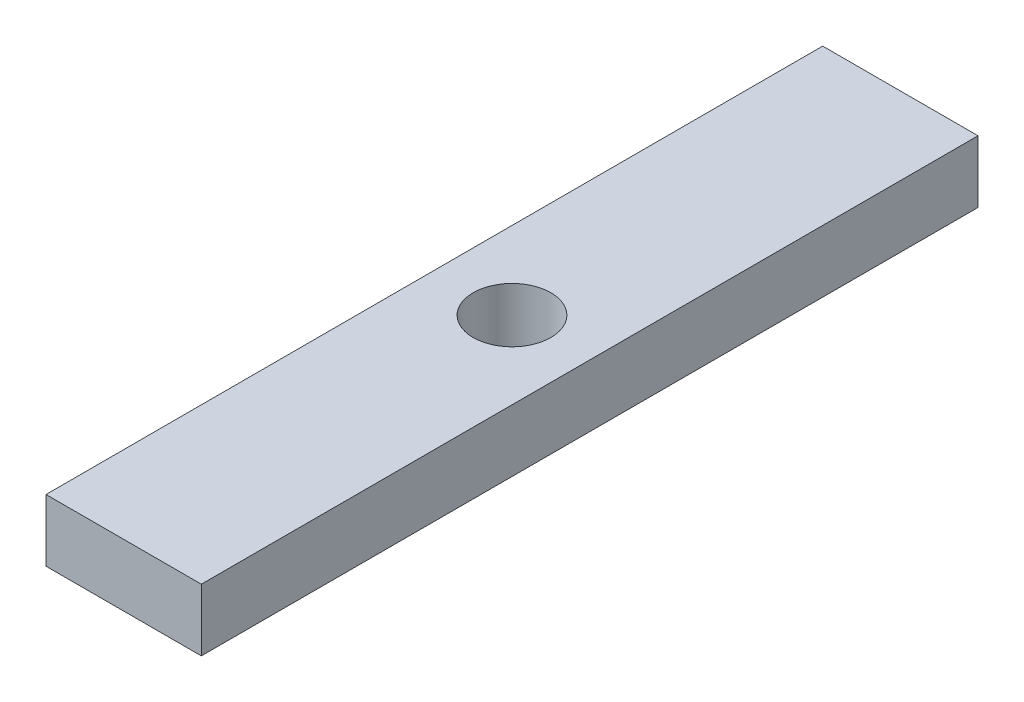
SolidWorks part; units mm, degrees
ref_plane "前视基准面" through (0, 0, 0) normal (0, 0, 1) x (1, 0, 0)
ref_plane "上视基准面" through (0, 0, 0) normal (0, 1, 0) x (1, 0, 0)
ref_plane "右视基准面" through (0, 0, 0) normal (1, 0, 0) x (0, 0, -1)
other "Configuration Table"
sketch "草图1" plane through (0, 0, 0) normal (0, 1, 0) x (1, 0, 0)
  line L1 (-10, 100) -> (10, 100)
  line L2 (-10, 100) -> (-10, 0)
  line L3 (-10, 0) -> (10, 0)
  line L4 (10, 100) -> (10, 0)
  point P4 (0, 0)
  dimension "D1" = 20
  dimension "D2" = 100
extrude "凸台-拉伸1" add sketch "草图1" along normal blind 8
sketch "草图2" plane through (0, 8, 0) normal (0, 1, 0) x (1, 0, 0)
  line L0 (10, 0) -> (10, 100) construction
  circle A0 centre (0, 50) radius 5
  point P4 (10, 50)
  dimension "D1" = 10
extrude "切除-拉伸1" cut sketch "草图2" against normal blind 10
